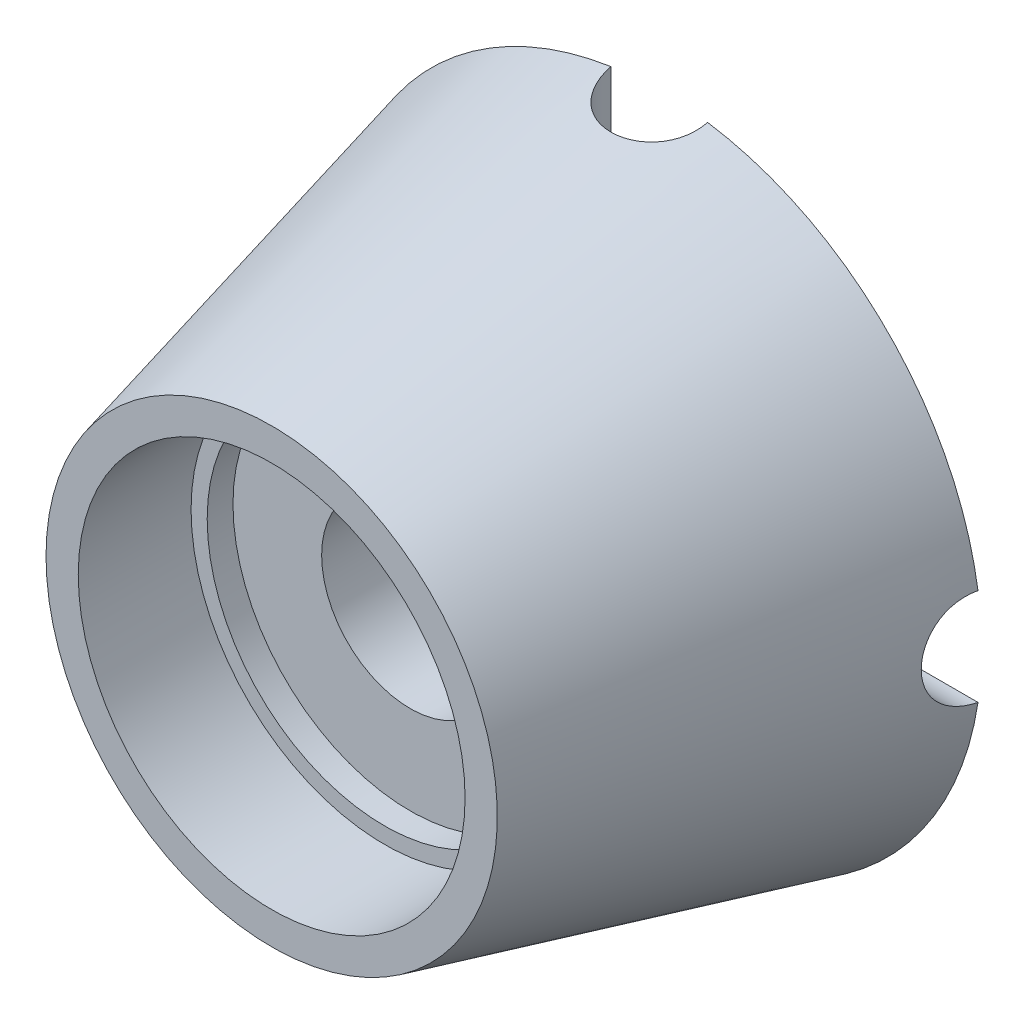
SolidWorks part; units mm, degrees
ref_plane "Front Plane" through (0, 0, 0) normal (0, 0, 1) x (1, 0, 0)
ref_plane "Top Plane" through (0, 0, 0) normal (0, 1, 0) x (1, 0, 0)
ref_plane "Right Plane" through (0, 0, 0) normal (1, 0, 0) x (0, 0, -1)
sketch "Sketch2" plane through (0, 0, 0) normal (0, 1, 0) x (1, 0, 0)
  line L0 (0, 120) -> (104.1702, 120) construction
  line L1 (0, 120) -> (0, 0) construction
  line L2 (76.5674, 108.9357) -> (65.106, 63)
  line L3 (65.106, 63) -> (27.5, 63)
  line L4 (27.5, 63) -> (27.5, 43)
  line L5 (27.5, 43) -> (55, 43)
  line L6 (55, 43) -> (55, 35)
  line L7 (55, 35) -> (60, 35)
  line L8 (60, 35) -> (60, 0)
  line L9 (60, 0) -> (70, 0)
  line L10 (70, 0) -> (96.7055, 107.0319)
  line L11 (76.5674, 108.9357) -> (79.3868, 120.2358)
  line L12 (79.3868, 120.2358) -> (100, 120.2358)
  line L13 (100, 120.2358) -> (96.7055, 107.0319)
  dimension "D1" = 120
  dimension "D2" = 20
  dimension "D3" = 20
  dimension "D4" = 8
  dimension "D5" = 35
  dimension "D6" = 55
  dimension "D7" = 27.5
  dimension "D8" = 60
  dimension "D9" = 70
  dimension "D10" = 100
revolve "Revolve2" add sketch "Sketch2" angle 360 about L1
sketch "Sketch5" plane through (0, 0, 0) normal (1, 0, 0) x (0, 0, -1)
  line L0 (120.2358, -100) -> (120.2358, 100) construction
  circle A0 centre (120.2358, 0) radius 15
extrude "Cut-Extrude3" cut sketch "Sketch5" against normal through all both and the other way through all
sketch "Sketch7" plane through (0, 0, 0) normal (0, 1, 0) x (1, 0, 0)
  line L0 (98.8686, 120.2358) -> (-98.8686, 120.2358) construction
  circle A0 centre (0, 120.2358) radius 15
  dimension "D1" = 30
extrude "Cut-Extrude4" cut sketch "Sketch7" against normal through all both and the other way through all
